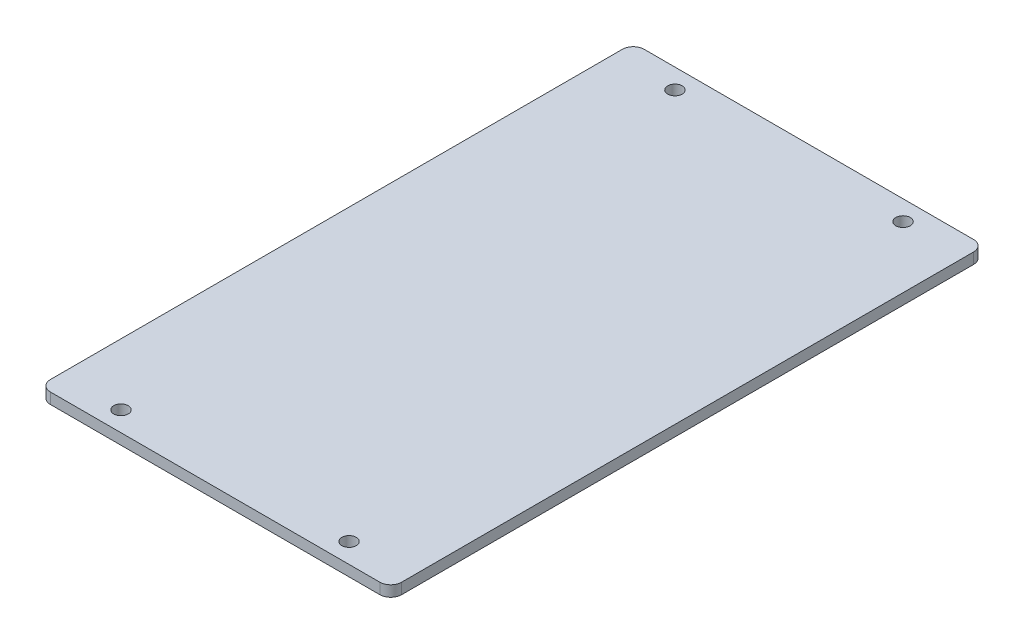
SolidWorks part; units mm, degrees
ref_plane "Front Plane" through (0, 0, 0) normal (0, 0, 1) x (1, 0, 0)
ref_plane "Top Plane" through (0, 0, 0) normal (0, 1, 0) x (1, 0, 0)
ref_plane "Right Plane" through (0, 0, 0) normal (1, 0, 0) x (0, 0, -1)
sketch "Sketch2" plane through (0, 0, 0) normal (0, 1, 0) x (1, 0, 0)
  line L1 (0, 0) -> (93, 0)
  line L2 (0, 0) -> (0, 37.5)
  line L12 (93, 0) -> (93, 160)
  line L17 (95, -2) -> (95, 162)
  line L18 (93, 0) -> (59, 0)
  line L19 (59, 0) -> (61, 0)
  line L20 (0, 37.5) -> (0, 137.5)
  line L21 (-2, 162) -> (95, 162)
  line L22 (-2, 137.5) -> (-2, 162)
  line L26 (-2, 37.5) -> (-2, 137.5)
  line L28 (0, 137.5) -> (0, 160)
  line L29 (0, 160) -> (93, 160)
  line L32 (70.5, 145) -> (93, 145) construction
  line L33 (22.5, 146.25) -> (0, 146.25) construction
  line L34 (-2, -2) -> (-2, 37.5)
  line L43 (-2, -2) -> (95, -2)
  line L44 (46.5, 0) -> (46.5, 160) construction
  line L46 (22.5, 146.25) -> (46.3551, 146.25) construction
  line L47 (70.5, 145) -> (46.6449, 145) construction
  line L52 (-2, 57.5) -> (-2, 102.5)
  line L66 (24, -2) -> (69, -2)
  circle A7 centre (15, 156.5215) radius 2
  circle A8 centre (78, 156.5215) radius 2
  circle A10 centre (78, 3.4785) radius 2
  circle A12 centre (15, 3.4785) radius 2
  dimension "D3" = 160
  dimension "D8" = 15
  dimension "D7" = 13.75
  dimension "D9" = 2
  dimension "D11" = 15
extrude "Boss-Extrude1" add sketch "Sketch2" along normal blind 3
fillet "Fillet12" radius 3 4 edges at (95, 1.5, -162) (95, 1.5, 2) (-2, 1.5, 2) (-2, 1.5, -162)
